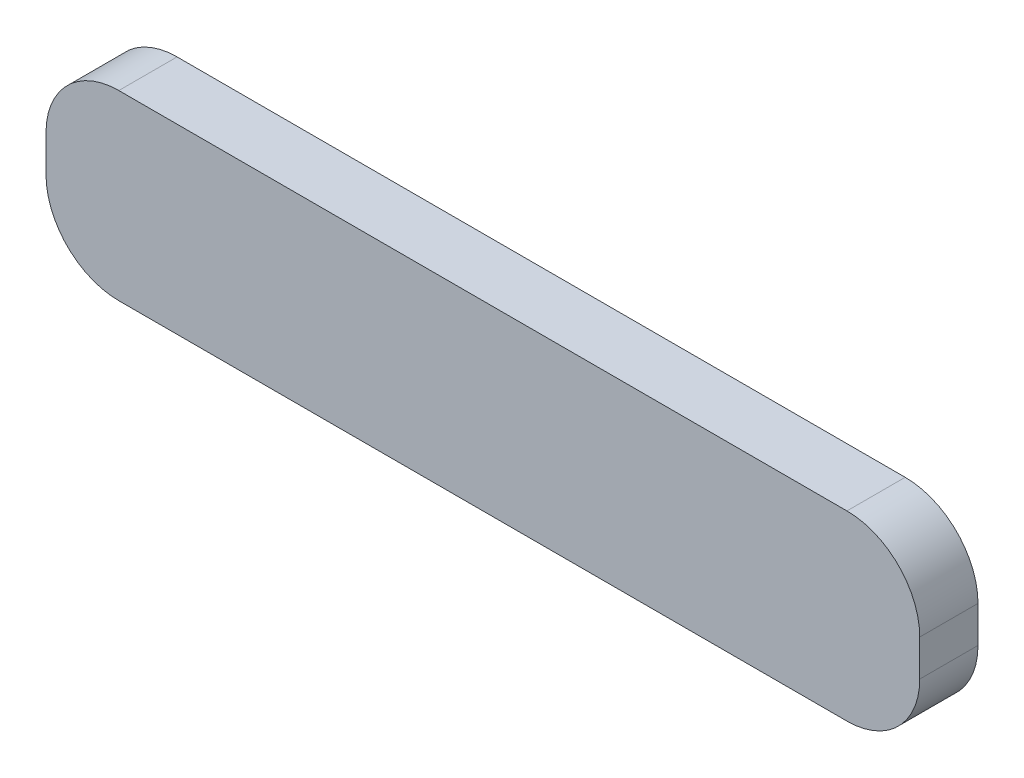
SolidWorks part; units mm, degrees
ref_plane "Front Plane" through (0, 0, 0) normal (0, 0, 1) x (1, 0, 0)
ref_plane "Top Plane" through (0, 0, 0) normal (0, 1, 0) x (1, 0, 0)
ref_plane "Right Plane" through (0, 0, 0) normal (1, 0, 0) x (0, 0, -1)
sketch "Sketch1" plane through (0, 0, 0) normal (0, 0, 1) x (1, 0, 0)
  line L1 (-59.5392, -8.1336) -> (60.4608, -8.1336)
  line L2 (-59.5392, -8.1336) -> (-59.5392, 16.8664)
  line L3 (-59.5392, 16.8664) -> (60.4608, 16.8664)
  line L4 (60.4608, -8.1336) -> (60.4608, 16.8664)
  dimension "D1" = 120
  dimension "D2" = 25
extrude "Boss-Extrude1" add sketch "Sketch1" along normal blind 8
fillet "Fillet1" radius 10 4 edges at (60.4608, -8.1336, 4) (60.4608, 16.8664, 4) (-59.5392, -8.1336, 4) (-59.5392, 16.8664, 4)
